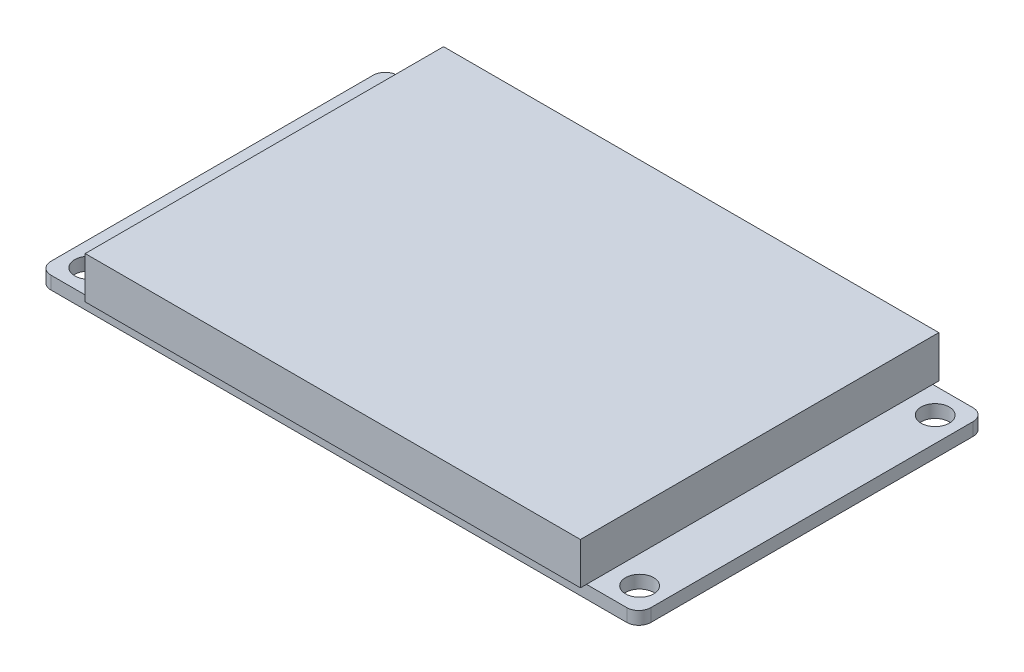
SolidWorks part; units mm, degrees
ref_plane "前视基准面" through (0, 0, 0) normal (0, 0, 1) x (1, 0, 0)
ref_plane "上视基准面" through (0, 0, 0) normal (0, 1, 0) x (1, 0, 0)
ref_plane "右视基准面" through (0, 0, 0) normal (1, 0, 0) x (0, 0, -1)
sketch "草图1" plane through (0, 0, 0) normal (0, 1, 0) x (1, 0, 0)
  line L0 (0, 21.5) -> (79.1565, 21.5) construction
  line L1 (1.5, 0) -> (73, 0)
  line L2 (0, 1.5) -> (0, 41.5)
  line L3 (1.5, 43) -> (73, 43)
  line L4 (74.5, 1.5) -> (74.5, 41.5)
  line L5 (37.25, 43) -> (37.25, -16.1851) construction
  arc A0 (74.5, 1.5) -> (73, 0) centre (73, 1.5) cw
  arc A1 (1.5, 0) -> (0, 1.5) centre (1.5, 1.5) cw
  arc A2 (74.5, 41.5) -> (73, 43) centre (73, 41.5) ccw
  arc A3 (1.5, 43) -> (0, 41.5) centre (1.5, 41.5) ccw
  circle A4 centre (3.05, 39.85) radius 1.75
  circle A5 centre (3.05, 3.15) radius 1.75
  circle A6 centre (71.45, 39.85) radius 1.75
  circle A7 centre (71.45, 3.15) radius 1.75
  point P7 (74.5, 0)
  point P10 (0, 0)
  point P13 (74.5, 43)
  point P28 (0, 0)
  point P29 (0, 0)
  point P30 (0, 0)
  dimension "D3" = 1.5
  dimension "D4" = 36.7
  dimension "D5" = 68.4
  dimension "D6" = 3.5
  dimension "D9" = 3.5
  dimension "D1" = 74.5
  dimension "D2" = 43
extrude "凸台-拉伸1" add sketch "草图1" along normal blind 1.6
sketch "草图2" plane through (0, 1.6, 0) normal (0, 1, 0) x (1, 0, 0)
  line L0 (37.25, 43) -> (37.25, 0) construction
  line L1 (73, 43) -> (1.5, 43) construction
  line L2 (1.5, 0) -> (73, 0) construction
  line L3 (0, 21.5) -> (74.5, 21.5) construction
  line L4 (0, 41.5) -> (0, 1.5) construction
  line L5 (74.5, 1.5) -> (74.5, 41.5) construction
  line L7 (6.5, 43.75) -> (68, 43.75)
  line L8 (6.5, 43.75) -> (6.5, -0.75)
  line L9 (6.5, -0.75) -> (68, -0.75)
  line L10 (68, 43.75) -> (68, -0.75)
  line L11 (6.5, 43.75) -> (68, -0.75) construction
  line L12 (6.5, -0.75) -> (68, 43.75) construction
  point P12 (37.25, 21.5)
  dimension "D1" = 44.5
  dimension "D2" = 61.5
extrude "凸台-拉伸2" add sketch "草图2" along normal blind 5.2
